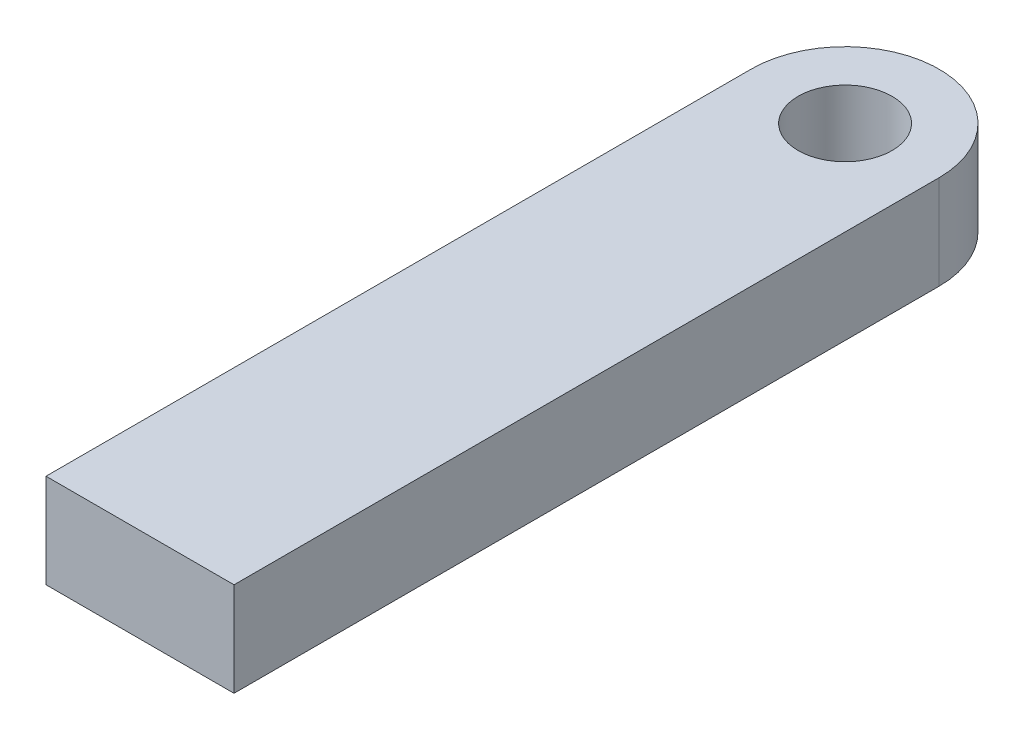
SolidWorks part; units mm, degrees
ref_plane "정면" through (0, 0, 0) normal (0, 0, 1) x (1, 0, 0)
ref_plane "윗면" through (0, 0, 0) normal (0, 1, 0) x (1, 0, 0)
ref_plane "우측면" through (0, 0, 0) normal (1, 0, 0) x (0, 0, -1)
sketch "스케치1" plane through (0, 0, 0) normal (0, 0, 1) x (1, 0, 0)
  line L1 (20, 10) -> (-20, 10)
  line L2 (20, 10) -> (20, -10)
  line L3 (20, -10) -> (-20, -10)
  line L4 (-20, 10) -> (-20, -10)
  line L5 (20, 10) -> (-20, -10) construction
  line L6 (20, -10) -> (-20, 10) construction
  dimension "D1" = 20
  dimension "D2" = 40
extrude "보스-돌출2" add sketch "스케치1" along normal blind 150
sketch "스케치5" plane through (0, 10, 0) normal (0, 1, 0) x (1, 0, 0)
  circle A1 centre (0, 0) radius 20
extrude "보스-돌출3" add sketch "스케치5" against normal blind 20
sketch "스케치6" plane through (0, 10, 0) normal (0, 1, 0) x (1, 0, 0)
  circle A0 centre (0, 0) radius 10
  dimension "D1" = 20
extrude "컷-돌출1" cut sketch "스케치6" against normal through all both and the other way through all
